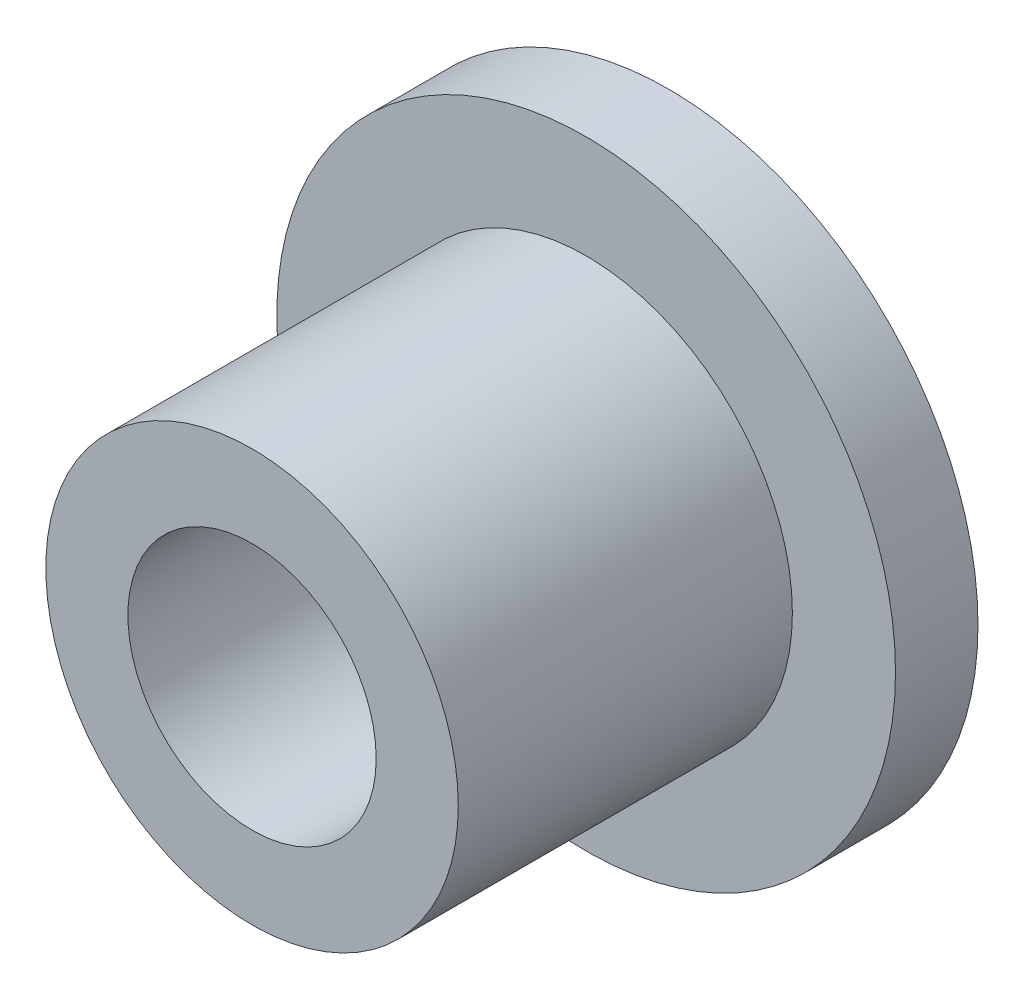
SolidWorks part; units mm, degrees
ref_plane "Front Plane" through (0, 0, 0) normal (0, 0, 1) x (1, 0, 0)
ref_plane "Top Plane" through (0, 0, 0) normal (0, 1, 0) x (1, 0, 0)
ref_plane "Right Plane" through (0, 0, 0) normal (1, 0, 0) x (0, 0, -1)
sketch "S01 - Steel load spreading flange" plane through (0, 0, 0) normal (0, 0, 1) x (1, 0, 0)
  circle A0 centre (0, 0) radius 7.5
  circle A1 centre (0, 0) radius 3.01
  dimension "D1" = 6.02
  dimension "D2" = 15
extrude "01 - Steel load spreading flange" add sketch "S01 - Steel load spreading flange" along normal blind 2
sketch "S02 - Stud bearing seat and crush sleeve" plane through (0, 0, 0) normal (0, 0, 1) x (1, 0, 0)
  circle A0 centre (0, 0) radius 5
  circle A1 centre (0, 0) radius 3.01
  dimension "D1" = 6.02
  dimension "D2" = 10
extrude "02 - Stud bearing seat and crush sleeve" add sketch "S02 - Stud bearing seat and crush sleeve" along normal blind 8.1 from offset 2
